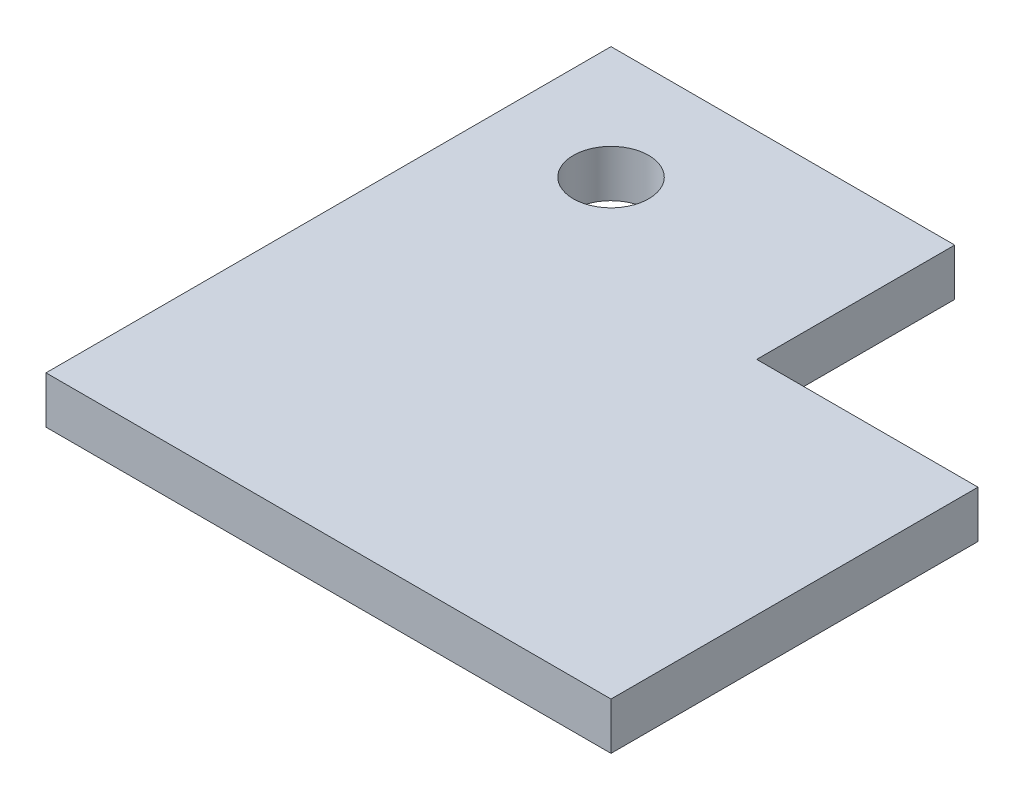
SolidWorks part; units mm, degrees
ref_plane "前视基准面" through (0, 0, 0) normal (0, 0, 1) x (1, 0, 0)
ref_plane "上视基准面" through (0, 0, 0) normal (0, 1, 0) x (1, 0, 0)
ref_plane "右视基准面" through (0, 0, 0) normal (1, 0, 0) x (0, 0, -1)
sketch "草图1" plane through (0, 0, 0) normal (0, 1, 0) x (1, 0, 0)
  line L1 (0, 0) -> (60, 0)
  line L2 (0, 0) -> (0, -60)
  line L3 (0, -60) -> (60, -60)
  line L4 (60, 0) -> (60, -60)
  circle A0 centre (12, -12) radius 4
  dimension "D1" = 8
  dimension "D2" = 12
  dimension "D3" = 12
  dimension "D4" = 60
  dimension "D5" = 60
extrude "凸台-拉伸1" add sketch "草图1" along normal blind 5
sketch "草图2" plane through (0, 0, 0) normal (0, 1, 0) x (1, 0, 0)
  line L0 (60, 0) -> (0, 0) construction
  line L1 (36.5, 0) -> (60, 0)
  line L2 (36.5, 0) -> (36.5, -21.03)
  line L3 (36.5, -21.03) -> (60, -21.03)
  line L4 (60, 0) -> (60, -21.03)
  line L5 (60, -60) -> (60, 0) construction
  dimension "D1" = 23.5
  dimension "D2" = 21.03
extrude "切除-拉伸1" cut sketch "草图2" along normal through all
